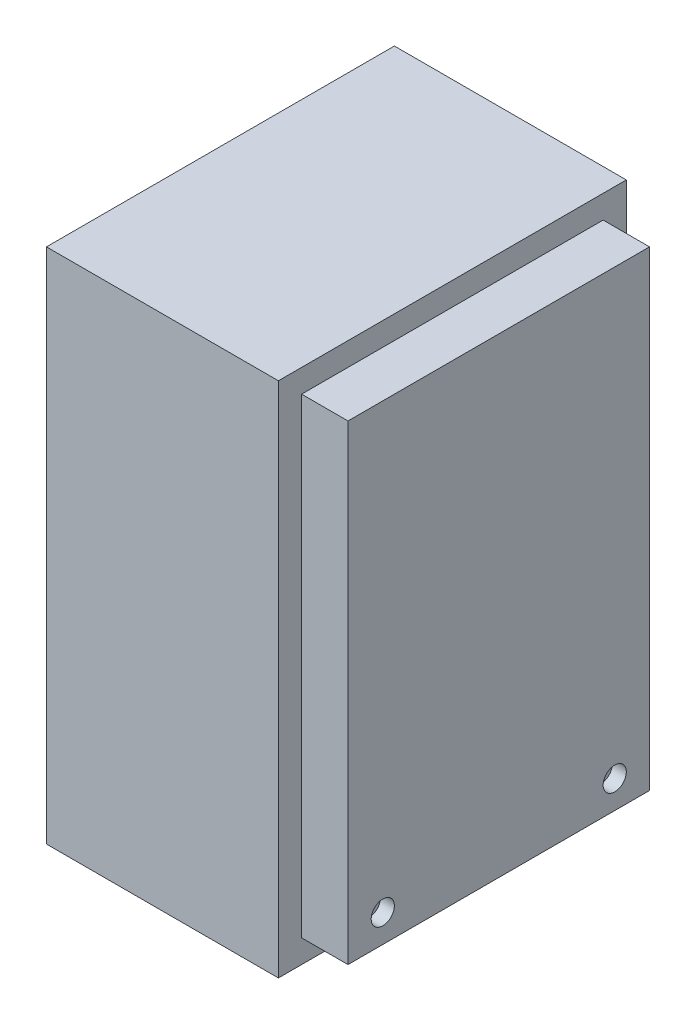
SolidWorks part; units mm, degrees
ref_plane "Alzado" through (0, 0, 0) normal (0, 0, 1) x (1, 0, 0)
ref_plane "Planta" through (0, 0, 0) normal (0, 1, 0) x (1, 0, 0)
ref_plane "Vista lateral" through (0, 0, 0) normal (1, 0, 0) x (0, 0, -1)
sketch "Croquis1" plane through (0, 0, 0) normal (1, 0, 0) x (0, 0, -1)
  line L1 (75, -111.5) -> (-75, -111.5)
  line L2 (75, -111.5) -> (75, 111.5)
  line L3 (75, 111.5) -> (-75, 111.5)
  line L4 (-75, -111.5) -> (-75, 111.5)
  line L5 (75, -111.5) -> (-75, 111.5) construction
  line L6 (75, 111.5) -> (-75, -111.5) construction
  point P0 (0, 0)
  dimension "D1" = 223
  dimension "D2" = 150
extrude "Saliente-Extruir1" add sketch "Croquis1" along normal blind 100
sketch "Croquis2" plane through (100, 0, 0) normal (1, 0, 0) x (0, 0, -1)
  line L0 (75, 111.5) -> (-75, 111.5) construction
  line L1 (65, -101.5) -> (-65, -101.5)
  line L2 (65, -101.5) -> (65, 101.5)
  line L3 (65, 101.5) -> (-65, 101.5)
  line L4 (-65, -101.5) -> (-65, 101.5)
  line L5 (65, -101.5) -> (-65, 101.5) construction
  line L6 (65, 101.5) -> (-65, -101.5) construction
  line L7 (-75, 111.5) -> (-75, -111.5) construction
  point P0 (0, 0)
  dimension "D1" = 10
  dimension "D2" = 10
extrude "Saliente-Extruir2" add sketch "Croquis2" along normal blind 20
sketch "Croquis3" plane through (120, 0, 0) normal (1, 0, 0) x (0, 0, -1)
  line L0 (-65, -101.5) -> (65, -101.5) construction
  line L1 (-65, -101.5) -> (65, -101.5) construction
  line L2 (-65, 101.5) -> (-65, -101.5) construction
  line L3 (65, -101.5) -> (65, 101.5) construction
  circle A0 centre (-50, -89.5) radius 5
  circle A1 centre (50, -89.5) radius 5
  dimension "D1" = 10
  dimension "D2" = 10
  dimension "D3" = 12
  dimension "D4" = 12
  dimension "D5" = 15
  dimension "D6" = 15
extrude "Cortar-Extruir1" cut sketch "Croquis3" against normal blind 6
